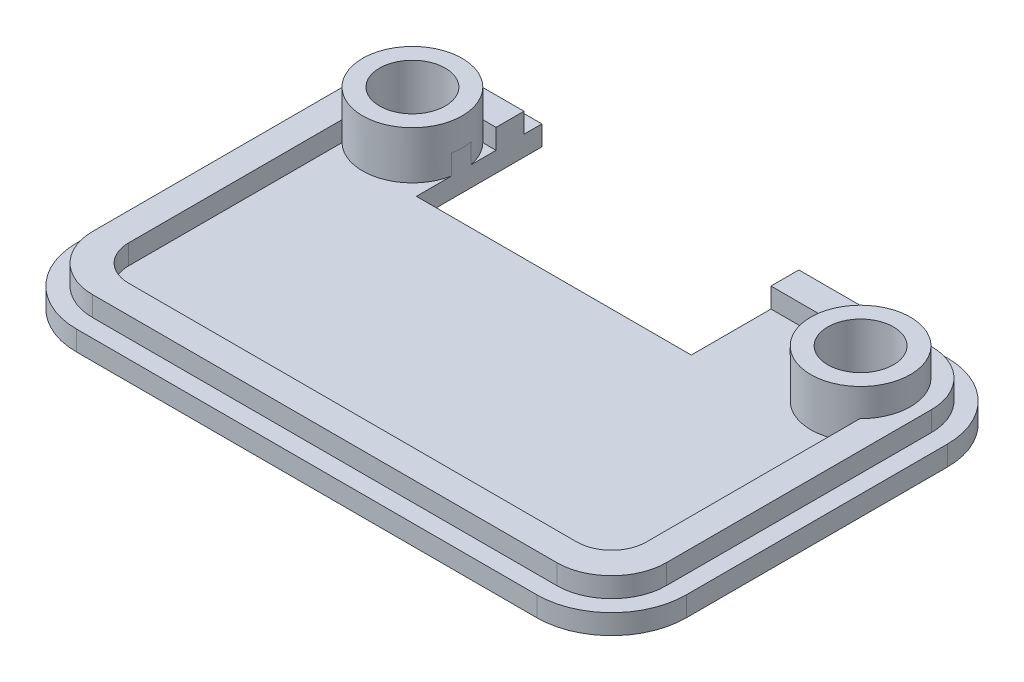
SolidWorks part; units mm, degrees
ref_plane "前视基准面" through (0, 0, 0) normal (0, 0, 1) x (1, 0, 0)
ref_plane "上视基准面" through (0, 0, 0) normal (0, 1, 0) x (1, 0, 0)
ref_plane "右视基准面" through (0, 0, 0) normal (1, 0, 0) x (0, 0, -1)
other "Configuration Table"
sketch "草图1" plane through (0, 0, 0) normal (0, 1, 0) x (1, 0, 0)
  line L1 (-15.3, 10.3) -> (15.3, 10.3)
  line L2 (-15.3, 10.3) -> (-15.3, -10.3)
  line L3 (-15.3, -10.3) -> (15.3, -10.3)
  line L4 (15.3, 10.3) -> (15.3, -10.3)
extrude "凸台-拉伸1" add sketch "草图1" along normal blind 1
sketch "草图2" plane through (0, 1, 0) normal (0, 1, 0) x (1, 0, 0)
  line L1 (-14.4, 9.4) -> (14.4, 9.4)
  line L2 (-14.4, 9.4) -> (-14.4, -9.4)
  line L3 (-14.4, -9.4) -> (14.4, -9.4)
  line L4 (14.4, 9.4) -> (14.4, -9.4)
  line L5 (-13, 8) -> (13, 8)
  line L6 (-13, 8) -> (-13, -8)
  line L7 (-13, -8) -> (13, -8)
  line L8 (13, 8) -> (13, -8)
  point P8 (0, 0)
extrude "凸台-拉伸2" add sketch "草图2" along normal blind 1
sketch "草图3" plane through (0, 1, 0) normal (0, 1, 0) x (1, 0, 0)
  circle A0 centre (-11.25, 6.25) radius 2.5
  circle A1 centre (-11.25, 6.25) radius 1.65
  circle A2 centre (11.25, 6.25) radius 2.5
  circle A3 centre (11.25, 6.25) radius 1.65
extrude "凸台-拉伸3" add sketch "草图3" along normal blind 2.4
fillet "圆角2" radius 2.75 4 edges at (14.4, 1.5, -9.4) (14.4, 1.5, 9.4) (-14.4, 1.5, 9.4) (-14.4, 1.5, -9.4)
fillet "圆角3" radius 3.75 4 edges at (-15.3, 0.5, 10.3) (15.3, 0.5, 10.3) (15.3, 0.5, -10.3) (-15.3, 0.5, -10.3)
fillet "圆角4" radius 1.75 2 edges at (13, 1.5, 8) (-13, 1.5, 8)
sketch "草图5" plane through (0, 0, 0) normal (0, -1, 0) x (1, 0, 0)
  line L1 (-8.8, -4) -> (5, -4)
  line L2 (-8.8, -4) -> (-8.8, -10.3)
  line L3 (-8.8, -10.3) -> (5, -10.3)
  line L4 (5, -4) -> (5, -10.3)
  line L6 (11.55, -10.3) -> (-11.55, -10.3) construction
  circle A0 centre (-11.25, -6.25) radius 1.65
  circle A1 centre (11.25, -6.25) radius 1.65
extrude "切除-拉伸1" cut sketch "草图5" against normal blind 2
